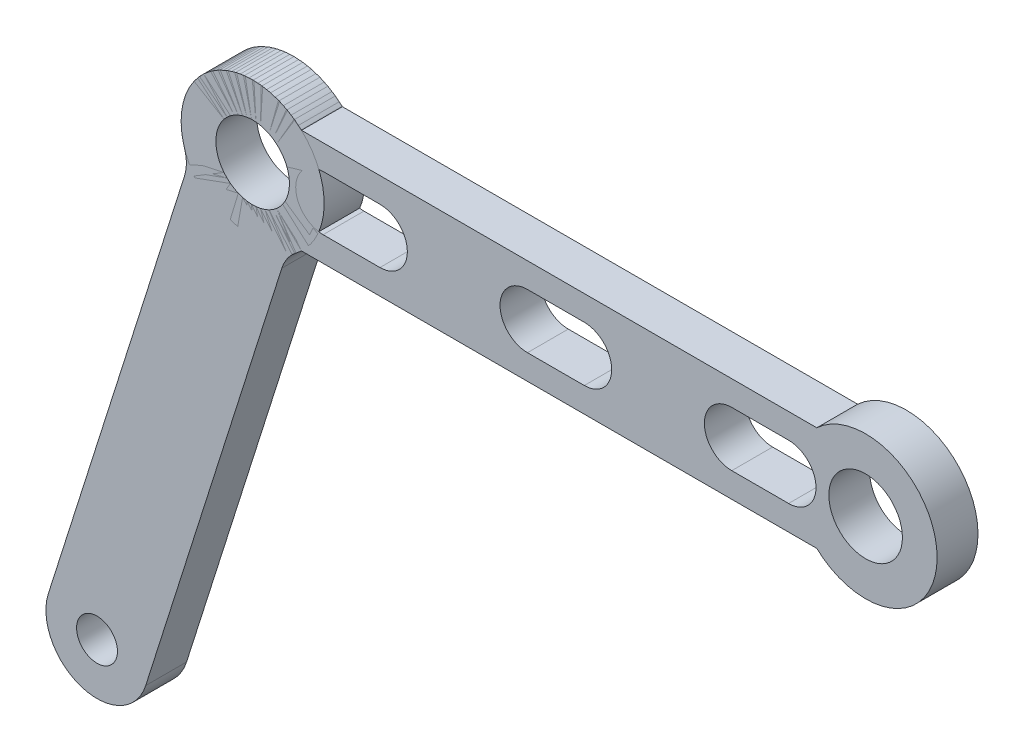
SolidWorks part; units mm, degrees
ref_plane "Front Plane" through (0, 0, 0) normal (0, 0, 1) x (1, 0, 0)
ref_plane "Top Plane" through (0, 0, 0) normal (0, 1, 0) x (1, 0, 0)
ref_plane "Right Plane" through (0, 0, 0) normal (1, 0, 0) x (0, 0, -1)
sketch "Sketch1" plane through (0, 0, 0) normal (0, 0, 1) x (1, 0, 0)
  line L0 (-70.6553, 0) -> (79.3447, 0) construction
  line L1 (55, 0) -> (-55, 0) construction
  line L2 (-53.413, 0) -> (-39.5014, 0) construction
  line L3 (-58.704, 12.7835) -> (67.3934, 12.7835)
  line L4 (-58.704, -12.7835) -> (67.3934, -12.7835)
  line L5 (-53.413, 6.7024) -> (-39.5014, 6.7024)
  line L6 (-53.413, -6.7024) -> (-39.5014, -6.7024)
  line L7 (-3.413, 0) -> (10.4986, 0) construction
  line L8 (-3.413, 6.7024) -> (10.4986, 6.7024)
  line L9 (-3.413, -6.7024) -> (10.4986, -6.7024)
  line L10 (46.587, 0) -> (60.4986, 0) construction
  line L11 (46.587, 6.7024) -> (60.4986, 6.7024)
  line L12 (46.587, -6.7024) -> (60.4986, -6.7024)
  arc A2 (-53.413, 6.7024) -> (-53.413, -6.7024) centre (-53.413, 0) ccw
  arc A3 (-39.5014, -6.7024) -> (-39.5014, 6.7024) centre (-39.5014, 0) ccw
  arc A4 (-3.413, 6.7024) -> (-3.413, -6.7024) centre (-3.413, 0) ccw
  arc A5 (10.4986, -6.7024) -> (10.4986, 6.7024) centre (10.4986, 0) ccw
  arc A6 (46.587, 6.7024) -> (46.587, -6.7024) centre (46.587, 0) ccw
  arc A7 (60.4986, -6.7024) -> (60.4986, 6.7024) centre (60.4986, 0) ccw
  arc A8 (-58.704, 12.7835) -> (-58.704, -12.7835) centre (-70.6553, 0) ccw
  arc A9 (67.3934, -12.7835) -> (67.3934, 12.7835) centre (79.3447, 0) ccw
  circle A10 centre (-70.6553, 0) radius 9
  circle A11 centre (79.3447, 0) radius 9
  point P7 (4.3447, 0)
  point P12 (-46.4572, 0)
  point P20 (3.5428, 0)
  point P27 (53.5428, 0)
  dimension "D2" = 18
  dimension "D1" = 3
extrude "Boss-Extrude3" add sketch "Sketch1" along normal blind 10
sketch "Sketch2" plane through (0, 0, 0) normal (0, 0, 1) x (1, 0, 0)
  line L1 (-70.6553, 0) -> (-73.3743, -8.5795) construction
  line L2 (-62.4395, -15.4515) -> (-96.8279, -123.9598)
  line L3 (-86.2713, -7.8988) -> (-120.6597, -116.407)
  circle A2 centre (-70.6553, 0) radius 9
  arc A5 (-62.4395, -15.4515) -> (-86.2713, -7.8988) centre (-70.6553, 0) ccw
  arc A6 (-120.6597, -116.407) -> (-96.8279, -123.9598) centre (-108.7438, -120.1834) ccw
  point P5 (-89.6996, -60.0917)
extrude "Boss-Extrude2" add sketch "Sketch2" along normal blind 10 separate body
sketch "Sketch3" plane through (0, 0, 10) normal (0, 0, 1) x (1, 0, 0)
  circle A0 centre (-108.7438, -120.1834) radius 5
extrude "Cut-Extrude1" cut sketch "Sketch3" against normal blind 10
fillet "Fillet1" radius 10 2 edges at (-86.2713, -7.8988, 5) (-62.4395, -15.4515, 5)
